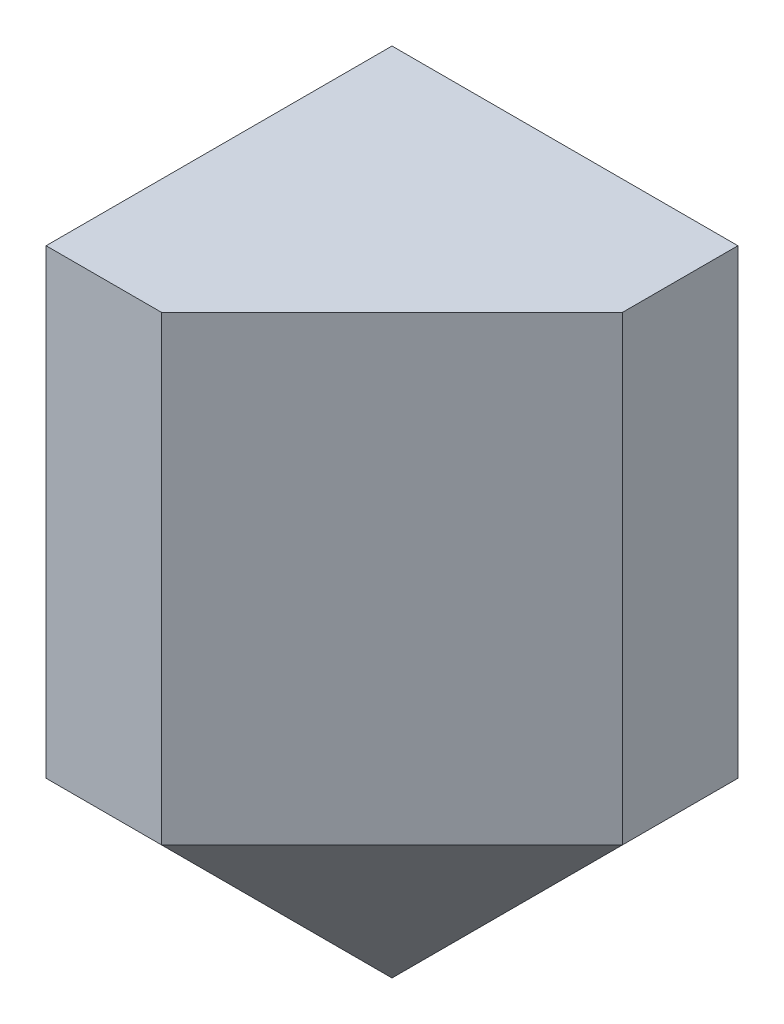
SolidWorks part; units mm, degrees
material "ABS"
ref_plane "Piano frontale" through (0, 0, 0) normal (0, 0, 1) x (1, 0, 0)
ref_plane "Piano superiore" through (0, 0, 0) normal (0, 1, 0) x (1, 0, 0)
ref_plane "Piano destro" through (0, 0, 0) normal (1, 0, 0) x (0, 0, -1)
sketch "Schizzo1" plane through (0, 0, 0) normal (0, 0, 1) x (1, 0, 0)
  line L1 (0, 0) -> (30, 0)
  line L2 (0, 0) -> (0, 40)
  line L3 (0, 40) -> (30, 40)
  line L4 (30, 0) -> (30, 40)
  dimension "D1" = 30
  dimension "D2" = 40
extrude "Estrusione-Estrusione1" add sketch "Schizzo1" along normal blind 30
chamfer "Smusso1" distance 20 angle 45 3 edges at (30, 20, 30) (30, 0, 15) (15, 0, 30)
sketch "Schizzo2" plane through (0, 40, 0) normal (0, 1, 0) x (1, 0, 0)
  line L0 (0, 0) -> (30, 0)
  line L1 (30, 0) -> (30, -10)
  line L2 (30, -10) -> (10, -30)
  line L3 (10, -30) -> (0, -30)
  line L4 (0, -30) -> (0, 0)
extrude "Estrusione-Estrusione2" add sketch "Schizzo2" along normal blind 20
hole_wizard "Foro per Vite M5-1" positions "Schizzo3" profile "Schizzo4" hole size "M5" standard "ISO"
sketch "Schizzo3" plane through (0, 0, 0) normal (-1, 0, 0) x (0, 0, 1)
  line L0 (18, 20) -> (18, 48) construction
  line L2 (0, 60) -> (0, 0) construction
  line L8 (18, 48) -> (14, 48) construction
  line L9 (0, 60) -> (30, 60) construction
  point P0 (18, 20)
  point P47 (14, 48)
  point P50 (6.9077, 48)
  point P51 (0, 0)
  point P52 (0, 0)
  point P53 (0, 0)
  point P54 (18, 33.8557)
  point P55 (0, 0)
  point P56 (18, 47.5835)
  point P57 (0, 0)
  point P58 (18, 47.8557)
  point P59 (0, 0)
  dimension "D1" = 18
  dimension "D2" = 4
  dimension "D3" = 12
  dimension "D4" = 28
sketch "Schizzo4" plane through (0, 20, 18) normal (0, 1, 0) x (0, 0, 1)
  line L0 (0, 0) -> (0, 14.6524)
  line L1 (0, 14.6524) -> (2.75, 13)
  line L2 (2.75, 13) -> (2.75, 0)
  line L5 (2.75, 0) -> (0, 0)
  line L10 (0, 14.6524) -> (-2.75, 13) construction
  line L11 (0, -6.35) -> (0, 107.95) construction
  dimension "Hole Dia." = 5.5
  dimension "Hole Depth" = 13
  dimension "Drill Angle" = 118
hole_wizard "Foro per Vite M5-2" positions "Schizzo3D1" profile "Schizzo5" hole size "M5" standard "ISO"
sketch3d "Schizzo3D1"
  line L0 (18, 20, 0) -> (18, 34, 0) construction
  line L2 (0, 60, 0) -> (0, 0, 0) construction
  line L4 (18, 48, 0) -> (18, 34, 0) construction
  line L5 (30, 60, 0) -> (0, 60, 0) construction
  point P2 (18, 20, 0)
  point P21 (18, 48, 0)
  dimension "D1" = 18
  dimension "D2" = 14
  dimension "D3" = 12
  dimension "D4" = 14
sketch "Schizzo5" plane through (18, 20, 0) normal (1, 0, 0) x (0, 1, 0)
  line L0 (0, 0) -> (0, 14.6524)
  line L1 (0, 14.6524) -> (2.75, 13)
  line L2 (2.75, 13) -> (2.75, 0)
  line L5 (2.75, 0) -> (0, 0)
  line L10 (0, 14.6524) -> (-2.75, 13) construction
  line L11 (0, -6.35) -> (0, 107.95) construction
  dimension "Hole Dia." = 5.5
  dimension "Hole Depth" = 13
  dimension "Drill Angle" = 118
